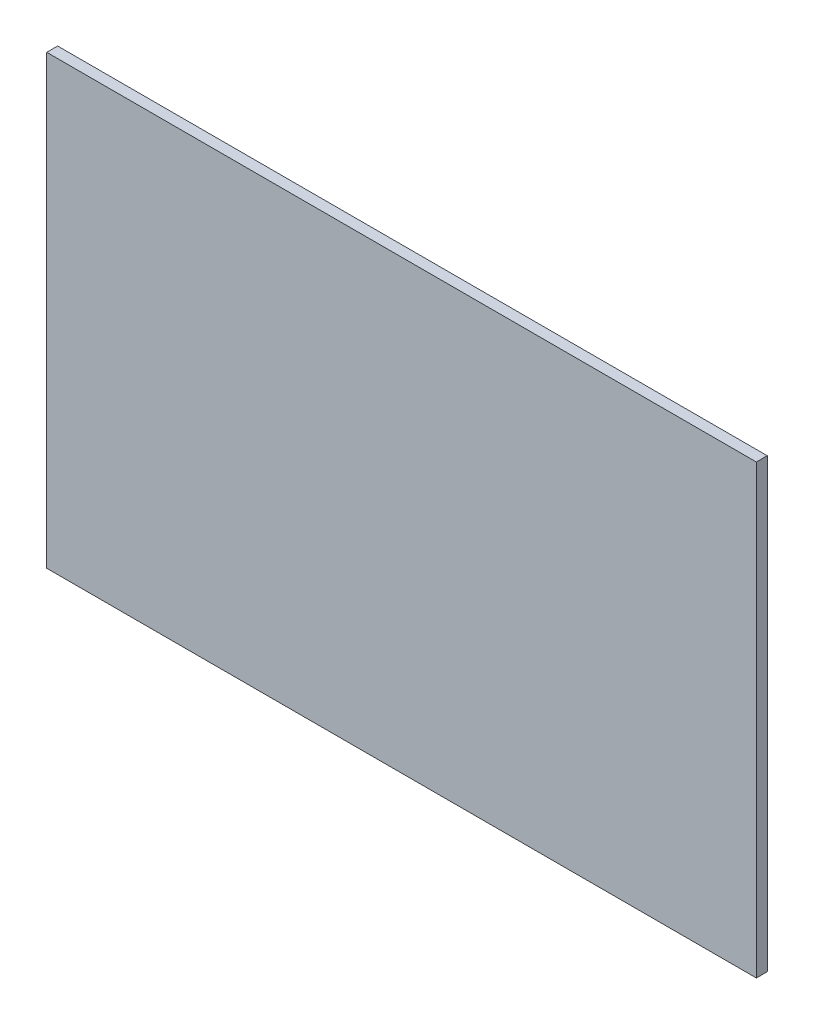
SolidWorks part; units mm, degrees
ref_plane "Front Plane" through (0, 0, 0) normal (0, 0, 1) x (1, 0, 0)
ref_plane "Top Plane" through (0, 0, 0) normal (0, 1, 0) x (1, 0, 0)
ref_plane "Right Plane" through (0, 0, 0) normal (1, 0, 0) x (0, 0, -1)
sketch "Sketch1" plane through (0, 0, 0) normal (0, 0, 1) x (1, 0, 0)
  line L1 (0, 0) -> (-228, 0)
  line L2 (0, 0) -> (0, 143.5723)
  line L3 (0, 143.5723) -> (-228, 143.5723)
  line L4 (-228, 0) -> (-228, 143.5723)
  dimension "D1" = 228
extrude "Boss-Extrude1" add sketch "Sketch1" along normal blind 3.5
